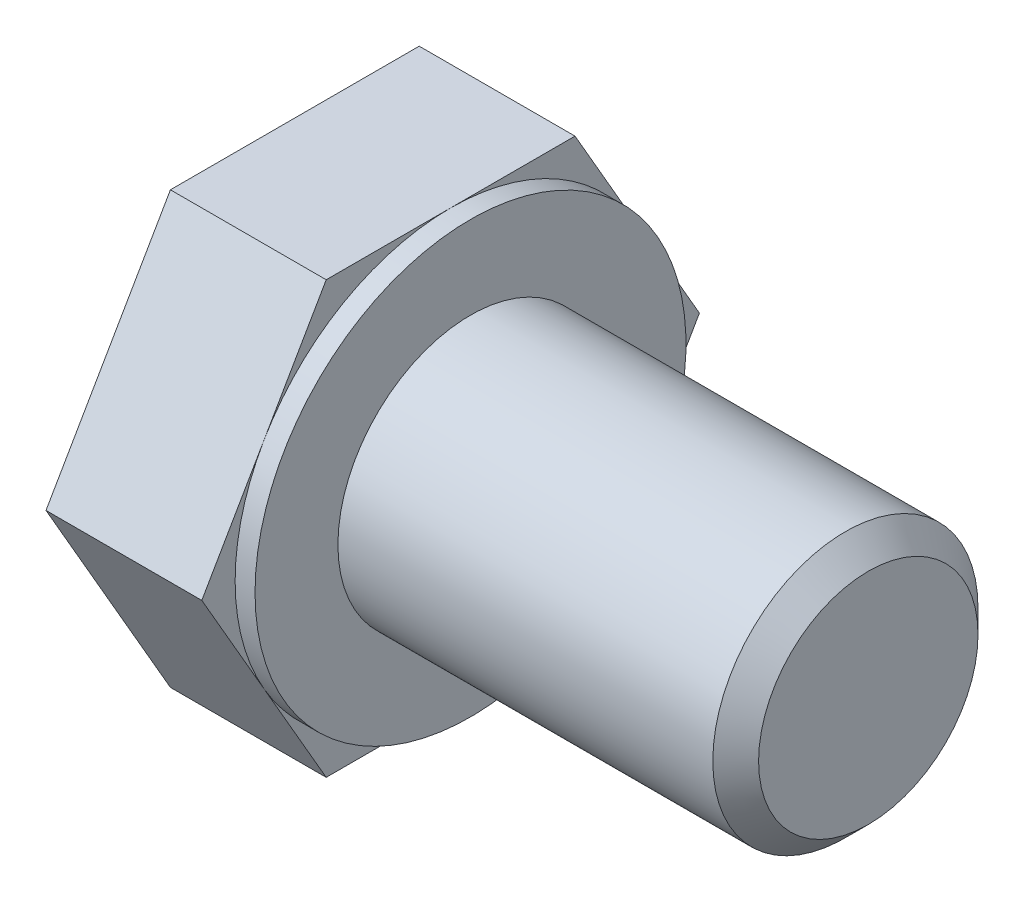
SolidWorks part; units mm, degrees
material "Alloy Steel"
ref_plane "Front Plane" through (0, 0, 0) normal (0, 0, 1) x (1, 0, 0)
ref_plane "Top Plane" through (0, 0, 0) normal (0, 1, 0) x (1, 0, 0)
ref_plane "Right Plane" through (0, 0, 0) normal (1, 0, 0) x (0, 0, -1)
sketch "BodySketch" plane through (0, 0, 0) normal (0, 1, 0) x (1, 0, 0)
  line L0 (0, 0) -> (12, 0) construction
  line L1 (11.3095, 4) -> (12, 3.3095)
  line L2 (0, 4) -> (0, 6.5)
  line L3 (0, 4) -> (11.3095, 4)
  line L4 (12, 0) -> (12, 3.3095)
  line L5 (0, 6.5) -> (-0.6, 6.5)
  line L6 (-0.6, 6.5) -> (-0.6, 0)
  line L7 (-0.6, 0) -> (12, 0)
  dimension "Diameter" = 8
  dimension "Body_ch_ang" = 45
  dimension "Width_flats" = 13
  dimension "Bearing_ht" = 0.6
  dimension "Length" = 12
revolve "BaseBody" add sketch "BodySketch" angle 360 about L0
cosmetic thread "Thread" parameters "Minor_dia"=6.619
sketch "HeadSketch" plane through (-0.6, 0, 0) normal (-1, 0, 0) x (0, 0, 1)
  line L1 (7.5056, 0) -> (3.7528, 6.5)
  line L2 (3.7528, 6.5) -> (-3.7528, 6.5)
  line L3 (-3.7528, 6.5) -> (-7.5056, 0)
  line L4 (-7.5056, 0) -> (-3.7528, -6.5)
  line L5 (-3.7528, -6.5) -> (3.7528, -6.5)
  line L6 (3.7528, -6.5) -> (7.5056, 0)
  circle A0 centre (0, 0) radius 6.5 construction
  circle A1 centre (0, 0) radius 6.5 construction
extrude "Hex" add sketch "HeadSketch" along normal blind 4.7
other "Freeze***"
other "PropertyManager"
